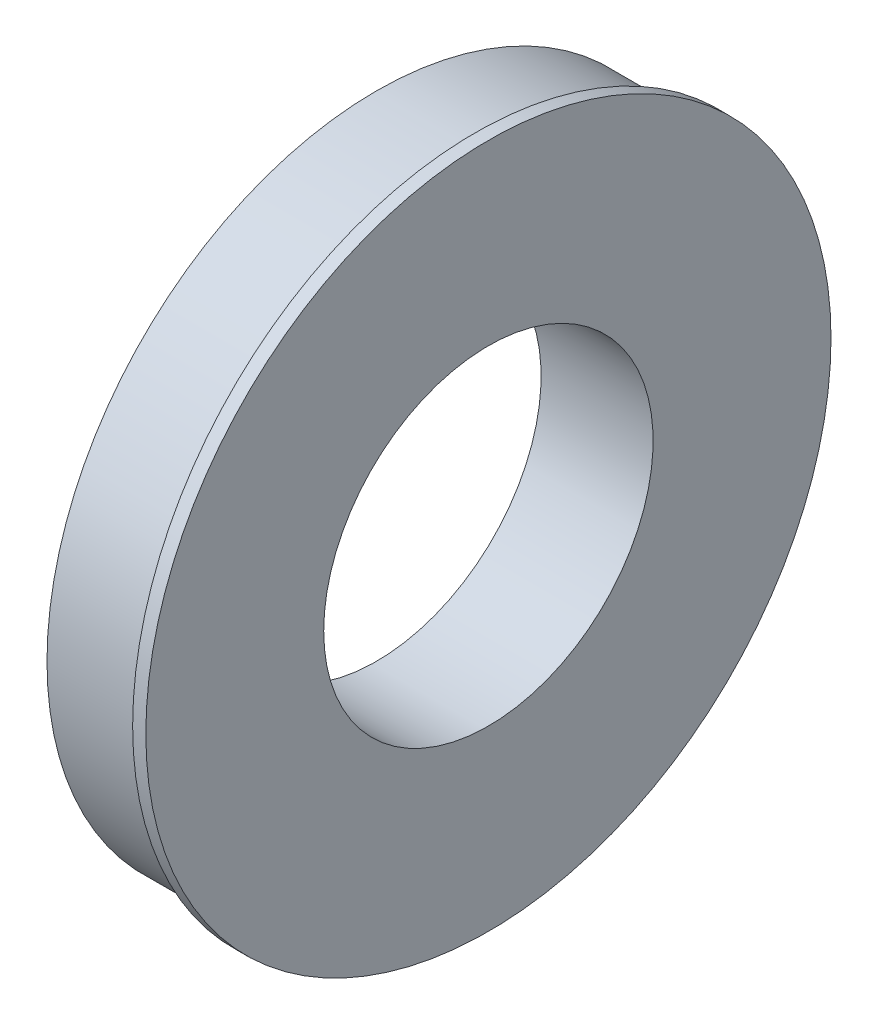
SolidWorks part; units mm, degrees
ref_plane "Front Plane" through (0, 0, 0) normal (0, 0, 1) x (1, 0, 0)
ref_plane "Top Plane" through (0, 0, 0) normal (0, 1, 0) x (1, 0, 0)
ref_plane "Right Plane" through (0, 0, 0) normal (1, 0, 0) x (0, 0, -1)
sketch "Sketch1" plane through (0, 0, 0) normal (1, 0, 0) x (0, 0, -1)
  circle A0 centre (0, 0) radius 31.75
  circle A1 centre (0, 0) radius 63.5
  dimension "D1" = 127
  dimension "D2" = 63.5
extrude "Boss-Extrude1" add sketch "Sketch1" along normal blind 19.05
sketch "Sketch2" plane through (19.05, 0, 0) normal (1, 0, 0) x (0, 0, -1)
  circle A1 centre (0, 0) radius 31.75 construction
  circle A2 centre (0, 0) radius 66.04
  circle A3 centre (0, 0) radius 66.04
  circle A4 centre (0, 0) radius 31.75
  dimension "D1" = 2.54
extrude "Boss-Extrude2" add sketch "Sketch2" along normal blind 2.54
